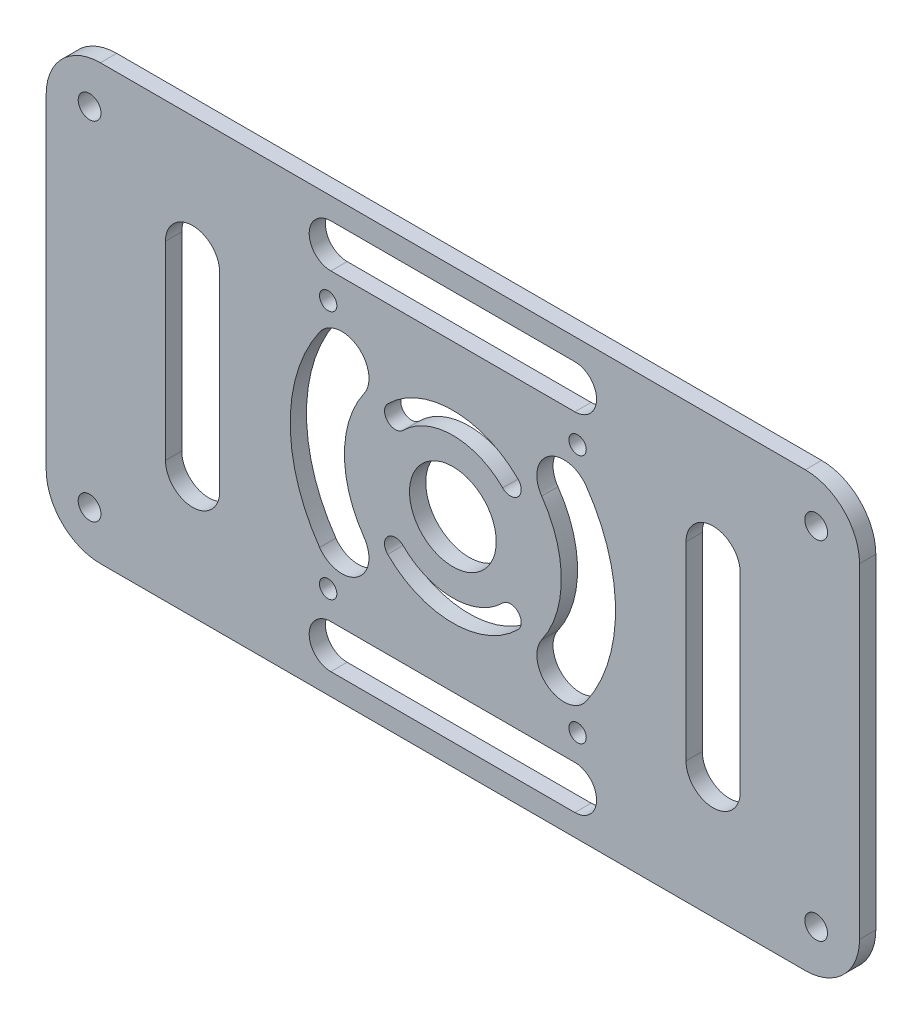
SolidWorks part; units mm, degrees
ref_plane "前视基准面" through (0, 0, 0) normal (0, 0, 1) x (1, 0, 0)
ref_plane "上视基准面" through (0, 0, 0) normal (0, 1, 0) x (1, 0, 0)
ref_plane "右视基准面" through (0, 0, 0) normal (1, 0, 0) x (0, 0, -1)
sketch "草图1" plane through (0, 0, 0) normal (0, 0, 1) x (1, 0, 0)
  line L0 (10, 0) -> (140, 0)
  line L1 (150, -10) -> (150, -70)
  line L2 (140, -80) -> (10, -80)
  line L3 (0, -70) -> (0, -10)
  line L4 (0, -40) -> (150, -40) construction
  line L5 (75, 0) -> (75, -80) construction
  arc A0 (10, -80) -> (0, -70) centre (10, -70) cw
  arc A1 (150, -70) -> (140, -80) centre (140, -70) cw
  arc A2 (140, 0) -> (150, -10) centre (140, -10) cw
  arc A3 (10, 0) -> (0, -10) centre (10, -10) ccw
  circle A4 centre (8, -8) radius 2.1
  circle A5 centre (8, -72) radius 2.1
  circle A6 centre (142, -72) radius 2.1
  circle A7 centre (142, -8) radius 2.1
  point P9 (150, -80)
  point P12 (150, 0)
  point P15 (0, 0)
  dimension "D3" = 10
  dimension "D4" = 4.2
  dimension "D5" = 8
  dimension "D1" = 150
  dimension "D2" = 80
  dimension "D6" = 8
extrude "凸台-拉伸1" add sketch "草图1" along normal blind 3
sketch "草图2" plane through (0, 0, 3) normal (0, 0, 1) x (1, 0, 0)
  line L0 (150, -40) -> (0, -40) construction
  line L1 (150, -70) -> (150, -10) construction
  line L2 (0, -10) -> (0, -70) construction
  line L3 (75, 0) -> (75, -80) construction
  line L4 (140, 0) -> (10, 0) construction
  line L5 (10, -80) -> (140, -80) construction
  line L7 (52, -63) -> (98, -63) construction
  line L8 (52, -63) -> (52, -17) construction
  line L9 (52, -17) -> (98, -17) construction
  line L10 (98, -63) -> (98, -17) construction
  line L11 (52, -63) -> (98, -17) construction
  line L12 (52, -17) -> (98, -63) construction
  circle A0 centre (52, -17) radius 1.6
  circle A1 centre (98, -17) radius 1.6
  circle A2 centre (98, -63) radius 1.6
  circle A3 centre (52, -63) radius 1.6
  circle A4 centre (75, -40) radius 8
  arc A5 (64.3934, -29.3934) -> (85.6066, -29.3934) centre (75, -40) cw construction
  arc A6 (87.0208, -27.9792) -> (62.9792, -27.9792) centre (75, -40) ccw
  arc A7 (84.1924, -30.8076) -> (65.8076, -30.8076) centre (75, -40) ccw
  arc A8 (84.1924, -30.8076) -> (87.0208, -27.9792) centre (85.6066, -29.3934) ccw
  arc A9 (62.9792, -27.9792) -> (65.8076, -30.8076) centre (64.3934, -29.3934) ccw
  arc A10 (64.3934, -50.6066) -> (85.6066, -50.6066) centre (75, -40) ccw construction
  arc A11 (87.0208, -52.0208) -> (62.9792, -52.0208) centre (75, -40) cw
  arc A12 (84.1924, -49.1924) -> (65.8076, -49.1924) centre (75, -40) cw
  arc A13 (84.1924, -49.1924) -> (87.0208, -52.0208) centre (85.6066, -50.6066) cw
  arc A14 (62.9792, -52.0208) -> (65.8076, -49.1924) centre (64.3934, -50.6066) cw
  point P12 (75, -40)
  point P25 (75, -25)
  point P32 (75, -55)
  dimension "D3" = 3.2
  dimension "D4" = 16
  dimension "D6" = 4
  dimension "D1" = 46
  dimension "D2" = 46
  dimension "D5" = 15
extrude "切除-拉伸1" cut sketch "草图2" against normal blind 3
sketch "草图3" plane through (0, 0, 3) normal (0, 0, 1) x (1, 0, 0)
  line L0 (75, -8) -> (75, -72) construction
  line L1 (8, -8) -> (142, -8) construction
  line L2 (8, -8) -> (8, -72) construction
  line L3 (8, -72) -> (142, -72) construction
  line L4 (142, -8) -> (142, -72) construction
  line L5 (142, -40) -> (8, -40) construction
  line L6 (75, -40) -> (95.4788, -54.3394) construction
  line L7 (75, -40) -> (95.4788, -25.6606) construction
  line L8 (123, -22.5) -> (123, -57.5) construction
  line L9 (128, -22.5) -> (128, -57.5)
  line L10 (118, -22.5) -> (118, -57.5)
  line L11 (27, -22.5) -> (27, -57.5) construction
  line L12 (22, -22.5) -> (22, -57.5)
  line L13 (32, -22.5) -> (32, -57.5)
  arc A0 (95.4788, -25.6606) -> (95.4788, -54.3394) centre (75, -40) cw construction
  arc A1 (99.5746, -57.2073) -> (99.5746, -22.7927) centre (75, -40) ccw
  arc A2 (91.383, -51.4715) -> (91.383, -28.5285) centre (75, -40) ccw
  arc A3 (91.383, -51.4715) -> (99.5746, -57.2073) centre (95.4788, -54.3394) ccw
  arc A4 (99.5746, -22.7927) -> (91.383, -28.5285) centre (95.4788, -25.6606) ccw
  arc A5 (128, -22.5) -> (118, -22.5) centre (123, -22.5) ccw
  arc A6 (118, -57.5) -> (128, -57.5) centre (123, -57.5) ccw
  arc A7 (22, -22.5) -> (32, -22.5) centre (27, -22.5) cw
  arc A8 (32, -57.5) -> (22, -57.5) centre (27, -57.5) cw
  arc A9 (54.5212, -25.6606) -> (54.5212, -54.3394) centre (75, -40) ccw construction
  arc A10 (50.4254, -57.2073) -> (50.4254, -22.7927) centre (75, -40) cw
  arc A11 (58.617, -51.4715) -> (58.617, -28.5285) centre (75, -40) cw
  arc A12 (58.617, -51.4715) -> (50.4254, -57.2073) centre (54.5212, -54.3394) cw
  arc A13 (50.4254, -22.7927) -> (58.617, -28.5285) centre (54.5212, -25.6606) cw
  point P14 (100, -40)
  point P21 (123, -40)
  point P26 (120.6613, -40)
  point P29 (27, -40)
  point P36 (50, -40)
  dimension "D3" = 10
  dimension "D1" = 35
  dimension "D2" = 25
  dimension "D4" = 48
  dimension "D5" = 35
  dimension "D6" = 10
extrude "切除-拉伸2" cut sketch "草图3" against normal blind 3
sketch "草图4" plane through (0, 0, 0) normal (0, 0, -1) x (-1, 0, 0)
  line L0 (-97.5, -8) -> (-52.5, -8) construction
  line L1 (-142, -8) -> (-8, -8) construction
  line L2 (-142, -8) -> (-142, -72) construction
  line L3 (-142, -72) -> (-8, -72) construction
  line L4 (-8, -8) -> (-8, -72) construction
  line L5 (-97.5, -4) -> (-52.5, -4)
  line L6 (-97.5, -12) -> (-52.5, -12)
  line L7 (-142, -40) -> (-8, -40) construction
  line L8 (-97.5, -72) -> (-52.5, -72) construction
  line L9 (-97.5, -76) -> (-52.5, -76)
  line L10 (-97.5, -68) -> (-52.5, -68)
  arc A0 (-97.5, -4) -> (-97.5, -12) centre (-97.5, -8) ccw
  arc A1 (-52.5, -12) -> (-52.5, -4) centre (-52.5, -8) ccw
  arc A2 (-97.5, -76) -> (-97.5, -68) centre (-97.5, -72) cw
  arc A3 (-52.5, -68) -> (-52.5, -76) centre (-52.5, -72) cw
  point P8 (-75, -8)
  point P14 (-75, -8)
  point P18 (-75, -72)
  dimension "D1" = 8
  dimension "D2" = 45
extrude "切除-拉伸3" cut sketch "草图4" against normal blind 3
